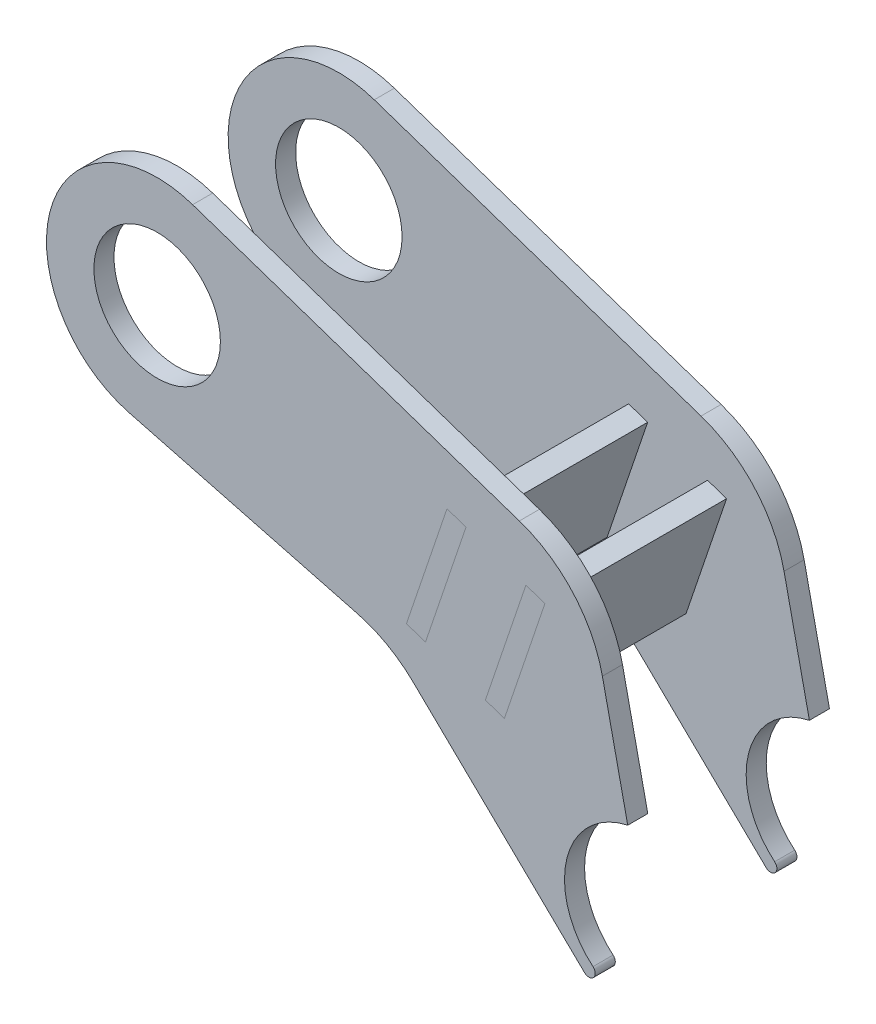
SolidWorks part; units mm, degrees
ref_plane "Front Plane" through (0, 0, 0) normal (0, 0, 1) x (1, 0, 0)
ref_plane "Top Plane" through (0, 0, 0) normal (0, 1, 0) x (1, 0, 0)
ref_plane "Right Plane" through (0, 0, 0) normal (1, 0, 0) x (0, 0, -1)
sketch "Sketch1" plane through (0, 0, 0) normal (0, 0, 1) x (1, 0, 0)
  line L17 (0, 0) -> (44.1306, -14.9292) construction
  line L22 (58.3116, -9.1699) -> (51.9025, -28.1151)
  line L23 (58.3116, -9.1699) -> (61.3192, -10.1873)
  line L28 (51.9025, -28.1151) -> (54.9101, -29.1326)
  line L29 (61.3192, -10.1873) -> (54.9101, -29.1326)
  line L30 (58.3116, -9.1699) -> (54.9101, -29.1326) construction
  line L31 (51.9025, -28.1151) -> (61.3192, -10.1873) construction
  line L32 (45.8314, -4.9479) -> (39.4223, -23.8931)
  line L33 (45.8314, -4.9479) -> (48.839, -5.9653)
  line L34 (39.4223, -23.8931) -> (42.4299, -24.9106)
  line L35 (48.839, -5.9653) -> (42.4299, -24.9106)
  line L36 (45.8314, -4.9479) -> (42.4299, -24.9106) construction
  line L37 (39.4223, -23.8931) -> (48.839, -5.9653) construction
  line L38 (5.608, 16.5771) -> (57.2714, -0.9004)
  line L39 (70.4048, -15.5924) -> (74.4109, -33.9993)
  line L40 (-4.4379, -16.9279) -> (31.6406, -26.3865)
  line L41 (40.4793, -31.3628) -> (67.574, -57.5917)
  line L42 (74.4109, -33.9993) -> (68.2696, -56.8732) construction
  circle A13 centre (0, 0) radius 10
  arc A19 (5.608, 16.5771) -> (-4.4379, -16.9279) centre (0, 0) ccw
  arc A20 (74.4109, -33.9993) -> (68.915, -56.1094) centre (77.1118, -46.4087) ccw
  arc A21 (31.6406, -26.3865) -> (40.4793, -31.3628) centre (26.5686, -45.7327) cw
  arc A22 (57.2714, -0.9004) -> (70.4048, -15.5924) centre (50.8623, -19.8457) cw
  arc A23 (67.574, -57.5917) -> (68.915, -56.1094) centre (68.2696, -56.8732) ccw
  point P9 (56.6108, -19.1512)
  point P12 (44.1306, -14.9292)
  dimension "D1" = 20
  dimension "D2" = 35
  dimension "D5" = 1
  dimension "D7" = 45
  dimension "D12" = 150.621
  dimension "D9" = 20
  dimension "D10" = 4
  dimension "D11" = 10
  dimension "D13" = 239.031
  dimension "D3" = 12.7
  dimension "D4" = 20
  dimension "D6" = 90
  dimension "D8" = 3.175
  dimension "D14" = 23.684
extrude "Boss-Extrude1" add sketch "Sketch1" along normal blind 3.175
ref_plane "Plane1" through (0, 0, -12.775) normal (0, 0, -1) x (-1, 0, 0)
mirror "Mirror3" about plane through (0, 0, -12.775) normal (0, 0, -1) of bodies 101
sketch "Sketch2" plane through (0, 0, 3.175) normal (0, 0, 1) x (1, 0, 0)
  line L13 (45.8314, -4.9479) -> (39.4223, -23.8931)
  line L14 (45.8314, -4.9479) -> (48.839, -5.9653)
  line L15 (39.4223, -23.8931) -> (42.4299, -24.9106)
  line L16 (48.839, -5.9653) -> (42.4299, -24.9106)
  line L17 (51.9025, -28.1151) -> (58.3116, -9.1699)
  line L18 (51.9025, -28.1151) -> (54.9101, -29.1326)
  line L19 (58.3116, -9.1699) -> (61.3192, -10.1873)
  line L20 (54.9101, -29.1326) -> (61.3192, -10.1873)
  line L21 (54.9101, -29.1326) -> (61.3192, -10.1873) construction
  line L22 (42.4299, -24.9106) -> (48.839, -5.9653) construction
ref_plane "Plane2" through (0, 0, -12.775) normal (0, 0, -1) x (-1, 0, 0)
extrude "Boss-Extrude2" add sketch "Sketch2" against normal up to surface (31.9 mm away) separate body contours L16 L15 L13 L14 | L20 L19 L17 L18 up to face at (43.4072, -23.753, -28.725)
